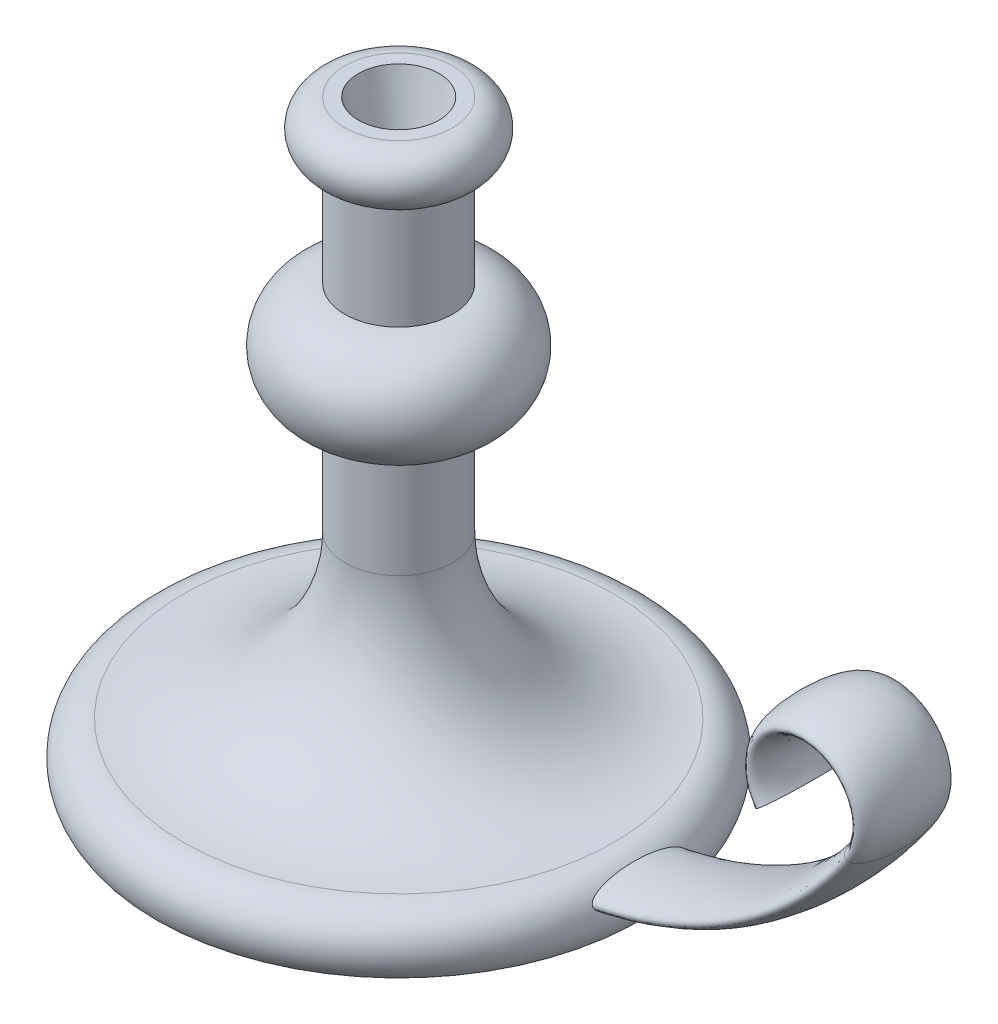
SolidWorks part; units mm, degrees
ref_plane "Front Plane" through (0, 0, 0) normal (0, 0, 1) x (1, 0, 0)
ref_plane "Top Plane" through (0, 0, 0) normal (0, 1, 0) x (1, 0, 0)
ref_plane "Right Plane" through (0, 0, 0) normal (1, 0, 0) x (0, 0, -1)
sketch "Sketch1" plane through (0, 0, 0) normal (0, 0, 1) x (1, 0, 0)
  line L0 (0, 0) -> (0, 220)
  line L1 (0, 220) -> (20, 220)
  line L2 (0, 0) -> (90, 0)
  line L3 (20, 200) -> (20, 160)
  line L4 (20, 120) -> (20, 80)
  arc A0 (20, 220) -> (20, 200) centre (20, 210) cw
  arc A1 (20, 160) -> (20, 120) centre (20, 140) cw
  arc A2 (20, 80) -> (80, 20) centre (80, 80) ccw
  arc A3 (80, 20) -> (90, 0) centre (80, 7.5) cw
  dimension "D4" = 10
  dimension "D5" = 20
  dimension "D7" = 60
  dimension "D8" = 12.5
  dimension "D1" = 20
  dimension "D2" = 220
  dimension "D3" = 90
  dimension "D6" = 40
  dimension "D9" = 80
revolve "Revolve1" add sketch "Sketch1" angle 360 about L0
sketch "Sketch2" plane through (0, 0, 0) normal (0, 0, 1) x (1, 0, 0)
  line L0 (0, 10) -> (60, 10)
  line L1 (0, 227.4356) -> (0, 175.1288) construction
  line L2 (-90, 0) -> (90, 0) construction
  arc A0 (60, 10) -> (183.5921, 75) centre (60, 160) ccw
  arc A1 (183.5921, 75) -> (150.6342, 75) centre (167.1131, 86.3333) ccw
  dimension "D2" = 150
  dimension "D4" = 20
  dimension "D1" = 60
  dimension "D3" = 65
  dimension "D5" = 10
sketch "Sketch3" plane through (0, 0, 0) normal (1, 0, 0) x (0, 0, -1)
  ellipse E0 centre (0, 10) end of major axis (17.5, 10) minor radius 5
  point P1 (0, 0)
  dimension "D1" = 35
  dimension "D2" = 10
sweep "Sweep1" add profiles "Sketch3" path "Sketch2"
sketch "Sketch4" plane through (0, 220, 0) normal (0, 1, 0) x (1, 0, 0)
  circle A0 centre (0, 0) radius 15
  dimension "D1" = 30
extrude "Cut-Extrude1" cut sketch "Sketch4" against normal blind 25 draft 15
